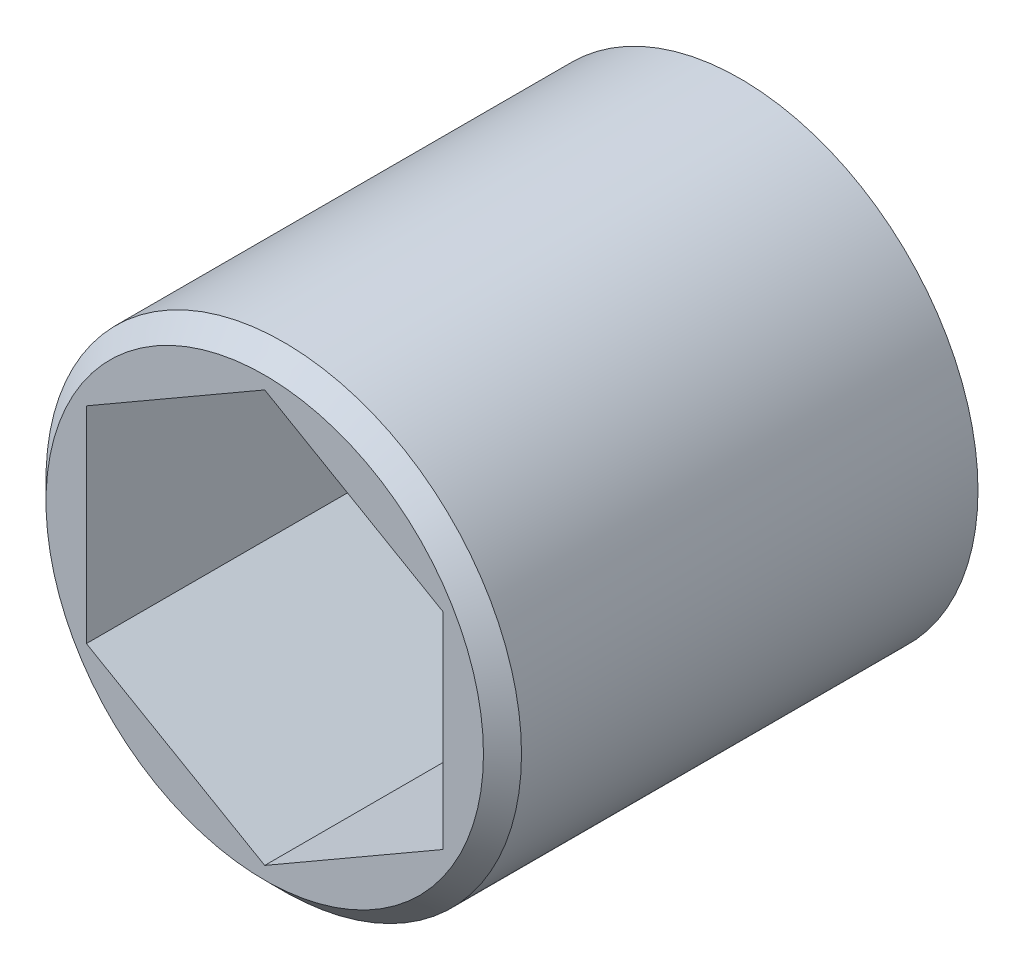
SolidWorks part; units mm, degrees
ref_plane "Front Plane" through (0, 0, 0) normal (0, 0, 1) x (1, 0, 0)
ref_plane "Top Plane" through (0, 0, 0) normal (0, 1, 0) x (1, 0, 0)
ref_plane "Right Plane" through (0, 0, 0) normal (1, 0, 0) x (0, 0, -1)
sketch "Sketch1" plane through (0, 0, 0) normal (0, 0, 1) x (1, 0, 0)
  circle A0 centre (0, 0) radius 6.35
  dimension "D1" = 12.7
extrude "Boss-Extrude1" add sketch "Sketch1" along normal blind 12.7
sketch "Sketch2" plane through (0, 0, 12.7) normal (0, 0, 1) x (1, 0, 0)
  line L1 (0, -5.4993) -> (4.7625, -2.7496)
  line L2 (4.7625, -2.7496) -> (4.7625, 2.7496)
  line L3 (4.7625, 2.7496) -> (0, 5.4993)
  line L4 (0, 5.4993) -> (-4.7625, 2.7496)
  line L5 (-4.7625, 2.7496) -> (-4.7625, -2.7496)
  line L6 (-4.7625, -2.7496) -> (0, -5.4993)
  circle A0 centre (0, 0) radius 4.7625 construction
  dimension "D1" = 9.525
extrude "Cut-Extrude1" cut sketch "Sketch2" against normal blind 9.525
sketch "Sketch3" plane through (0, 0, 3.175) normal (0, 0, 1) x (1, 0, 0)
  line L1 (-2.54, 2.54) -> (2.54, 2.54)
  line L2 (-2.54, 2.54) -> (-2.54, -2.54)
  line L3 (-2.54, -2.54) -> (2.54, -2.54)
  line L4 (2.54, 2.54) -> (2.54, -2.54)
  line L5 (-2.54, 2.54) -> (2.54, -2.54) construction
  line L6 (-2.54, -2.54) -> (2.54, 2.54) construction
  point P0 (0, 0)
  dimension "D1" = 5.08
  dimension "D2" = 5.08
extrude "Cut-Extrude2" cut sketch "Sketch3" against normal blind 9.525
sketch "Sketch4" [suppressed] plane through (0, 0, 0) normal (0, 0, 1) x (1, 0, 0)
  circle A0 centre (0, 0) radius 7.9375
  dimension "D1" = 15.875
extrude "Boss-Extrude2" [suppressed] add sketch "Sketch4" along normal blind 19.05
sketch "Sketch5" [suppressed] plane through (0, 0, 19.05) normal (0, 0, 1) x (1, 0, 0)
  line L1 (0, -7.3323) -> (6.35, -3.6662)
  line L2 (6.35, -3.6662) -> (6.35, 3.6662)
  line L3 (6.35, 3.6662) -> (0, 7.3323)
  line L4 (0, 7.3323) -> (-6.35, 3.6662)
  line L5 (-6.35, 3.6662) -> (-6.35, -3.6662)
  line L6 (-6.35, -3.6662) -> (0, -7.3323)
  circle A0 centre (0, 0) radius 6.35 construction
  dimension "D1" = 12.7
extrude "Cut-Extrude3" [suppressed] cut sketch "Sketch5" against normal blind 12.7
sketch "Sketch6" [suppressed] plane through (0, 0, 6.35) normal (0, 0, 1) x (1, 0, 0)
  line L1 (-2.54, 2.54) -> (2.54, 2.54)
  line L2 (-2.54, 2.54) -> (-2.54, -2.54)
  line L3 (-2.54, -2.54) -> (2.54, -2.54)
  line L4 (2.54, 2.54) -> (2.54, -2.54)
  line L5 (-2.54, 2.54) -> (2.54, -2.54) construction
  line L6 (-2.54, -2.54) -> (2.54, 2.54) construction
  point P0 (0, 0)
  dimension "D1" = 5.08
  dimension "D2" = 5.08
extrude "Cut-Extrude4" [suppressed] cut sketch "Sketch6" against normal through all
sketch "Sketch7" [suppressed] plane through (0, 0, 0) normal (0, 0, 1) x (1, 0, 0)
  circle A0 centre (0, 0) radius 11.1125
  dimension "D1" = 22.225
extrude "Boss-Extrude3" [suppressed] add sketch "Sketch7" along normal blind 25.4
sketch "Sketch8" [suppressed] plane through (0, 0, 25.4) normal (0, 0, 1) x (1, 0, 0)
  line L1 (0, -10.9985) -> (9.525, -5.4993)
  line L2 (9.525, -5.4993) -> (9.525, 5.4993)
  line L3 (9.525, 5.4993) -> (0, 10.9985)
  line L4 (0, 10.9985) -> (-9.525, 5.4993)
  line L5 (-9.525, 5.4993) -> (-9.525, -5.4993)
  line L6 (-9.525, -5.4993) -> (0, -10.9985)
  circle A0 centre (0, 0) radius 9.525 construction
  dimension "D1" = 19.05
extrude "Cut-Extrude5" [suppressed] cut sketch "Sketch8" against normal blind 19.05
sketch "Sketch9" [suppressed] plane through (0, 0, 6.35) normal (0, 0, 1) x (1, 0, 0)
  line L1 (-2.54, 2.54) -> (2.54, 2.54)
  line L2 (-2.54, 2.54) -> (-2.54, -2.54)
  line L3 (-2.54, -2.54) -> (2.54, -2.54)
  line L4 (2.54, 2.54) -> (2.54, -2.54)
  line L5 (-2.54, 2.54) -> (2.54, -2.54) construction
  line L6 (-2.54, -2.54) -> (2.54, 2.54) construction
  point P0 (0, 0)
  dimension "D1" = 5.08
  dimension "D2" = 5.08
extrude "Cut-Extrude6" [suppressed] cut sketch "Sketch9" against normal through all
sketch "Sketch10" [suppressed] plane through (0, 0, 0) normal (0, 0, 1) x (1, 0, 0)
  circle A0 centre (0, 0) radius 15.875
  dimension "D1" = 31.75
extrude "Boss-Extrude4" [suppressed] add sketch "Sketch10" along normal blind 31.75
sketch "Sketch11" [suppressed] plane through (0, 0, 31.75) normal (0, 0, 1) x (1, 0, 0)
  line L1 (15.3979, 0) -> (7.699, 13.335)
  line L2 (7.699, 13.335) -> (-7.699, 13.335)
  line L3 (-7.699, 13.335) -> (-15.3979, 0)
  line L4 (-15.3979, 0) -> (-7.699, -13.335)
  line L5 (-7.699, -13.335) -> (7.699, -13.335)
  line L6 (7.699, -13.335) -> (15.3979, 0)
  circle A0 centre (0, 0) radius 13.335 construction
  dimension "D1" = 26.67
extrude "Cut-Extrude7" [suppressed] cut sketch "Sketch11" against normal blind 25.4
sketch "Sketch13" [suppressed] plane through (0, 0, 6.35) normal (0, 0, 1) x (1, 0, 0)
  line L1 (-2.54, 2.54) -> (2.54, 2.54)
  line L2 (-2.54, 2.54) -> (-2.54, -2.54)
  line L3 (-2.54, -2.54) -> (2.54, -2.54)
  line L4 (2.54, 2.54) -> (2.54, -2.54)
  line L5 (-2.54, 2.54) -> (2.54, -2.54) construction
  line L6 (-2.54, -2.54) -> (2.54, 2.54) construction
  point P0 (0, 0)
  dimension "D1" = 5.08
  dimension "D2" = 5.08
extrude "Cut-Extrude8" [suppressed] cut sketch "Sketch13" against normal blind 25.4
chamfer "Chamfer1" distance 0.508 angle 45 1 edges at (6.35, 0, 12.7)
chamfer "Chamfer2" [suppressed] distance 0.508 angle 45
chamfer "Chamfer3" [suppressed] distance 0.508 angle 45
chamfer "Chamfer4" [suppressed] distance 0.508 angle 45
